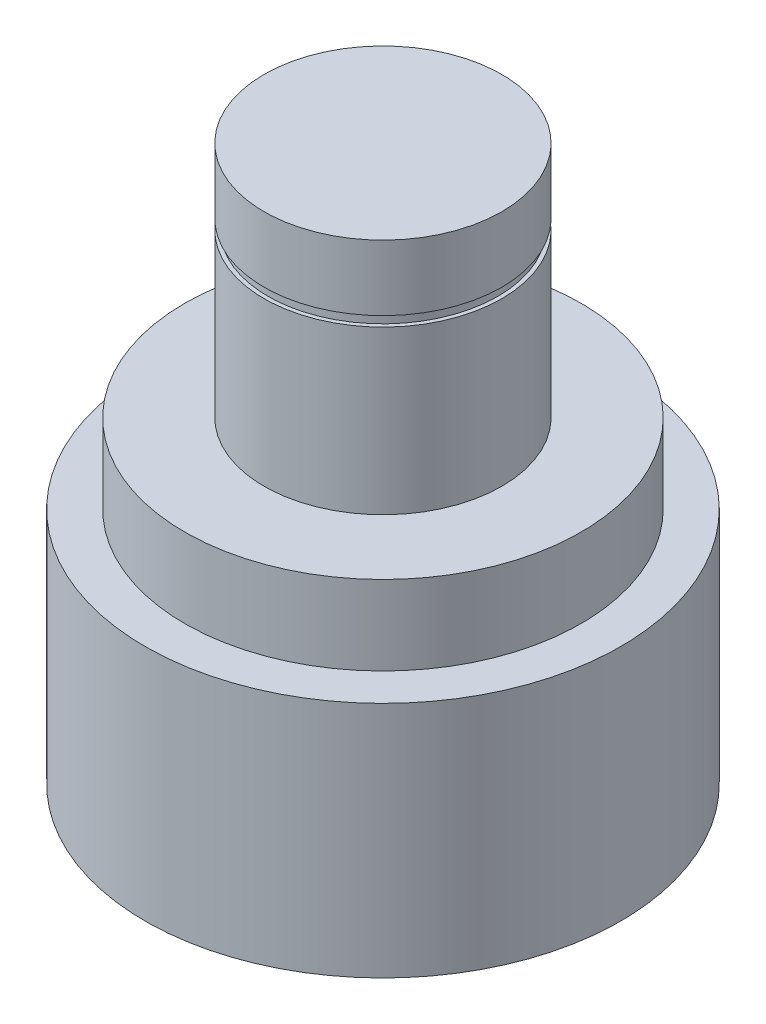
SolidWorks part; units mm, degrees
ref_plane "Front" through (0, 0, 0) normal (0, 0, 1) x (1, 0, 0)
ref_plane "Top" through (0, 0, 0) normal (0, 1, 0) x (1, 0, 0)
ref_plane "Right" through (0, 0, 0) normal (1, 0, 0) x (0, 0, -1)
sketch "Sketch1" plane through (0, 0, 0) normal (0, 0, 1) x (1, 0, 0)
  line L0 (0, 0) -> (-6, 0)
  line L1 (-6, 0) -> (-6, 6)
  line L2 (-6, 6) -> (-5, 6)
  line L3 (-5, 8) -> (-3, 8)
  line L4 (0, 14) -> (0, 0) construction
  line L5 (0, 14) -> (0, 0)
  line L6 (-3, 8) -> (-3, 12.1)
  line L7 (-3, 14) -> (0, 14)
  line L8 (0, 0) -> (0, 14) construction
  line L9 (-3, 12.35) -> (-3, 14)
  line L10 (-3, 12.35) -> (-2.9, 12.35)
  line L11 (-5, 6) -> (-5, 8)
  line L12 (-3, 12.1) -> (-2.9, 12.1)
  line L13 (-2.9, 12.35) -> (-2.9, 12.1)
  dimension "D1" = 10
  dimension "D2" = 8
  dimension "D3" = 6
  dimension "D4" = 6
  dimension "D5" = 12
  dimension "D6" = 6
  dimension "D7" = 4.1
  dimension "D8" = 0.25
  dimension "D9" = 0.1
revolve "Revolve1" add sketch "Sketch1" angle 360 about L4
